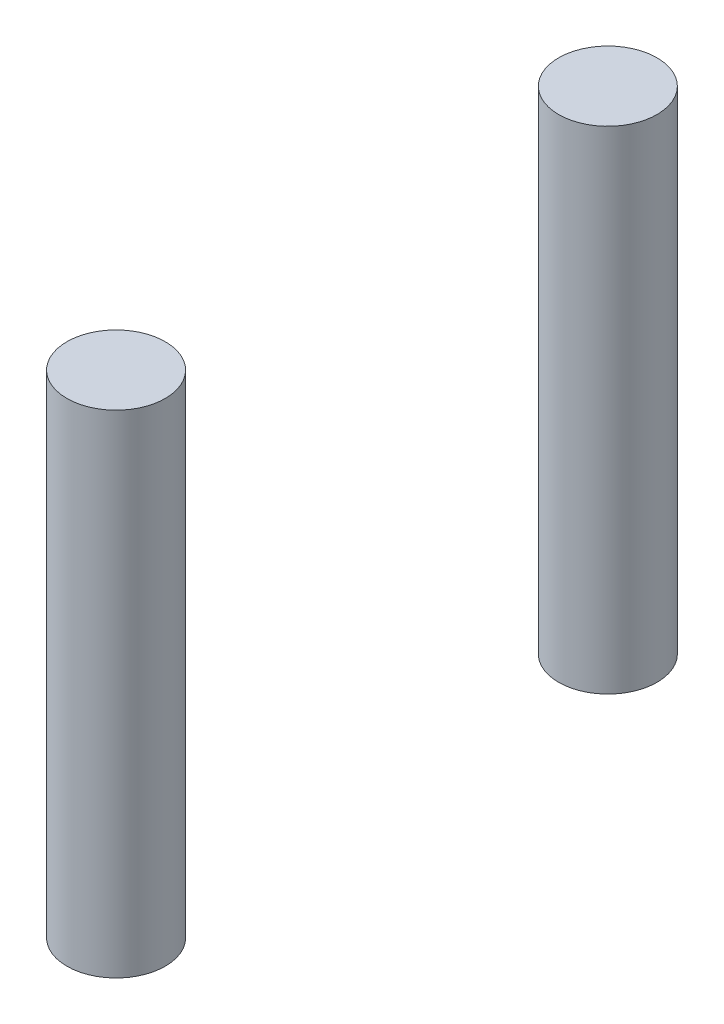
SolidWorks part; units mm, degrees
ref_plane "Спереди" through (0, 0, 0) normal (0, 0, 1) x (1, 0, 0)
ref_plane "Сверху" through (0, 0, 0) normal (0, 1, 0) x (1, 0, 0)
ref_plane "Справа" through (0, 0, 0) normal (1, 0, 0) x (0, 0, -1)
sketch "Эскиз1" plane through (0, 0, 0) normal (0, 1, 0) x (1, 0, 0)
  line L0 (0, 0) -> (0, 5) construction
  line L1 (0, 0) -> (0, -5) construction
  circle A1 centre (0, -5) radius 1
  circle A2 centre (0, 5) radius 1
extrude "Бобышка-Вытянуть3" add sketch "Эскиз1" against normal blind 10 from offset 3
